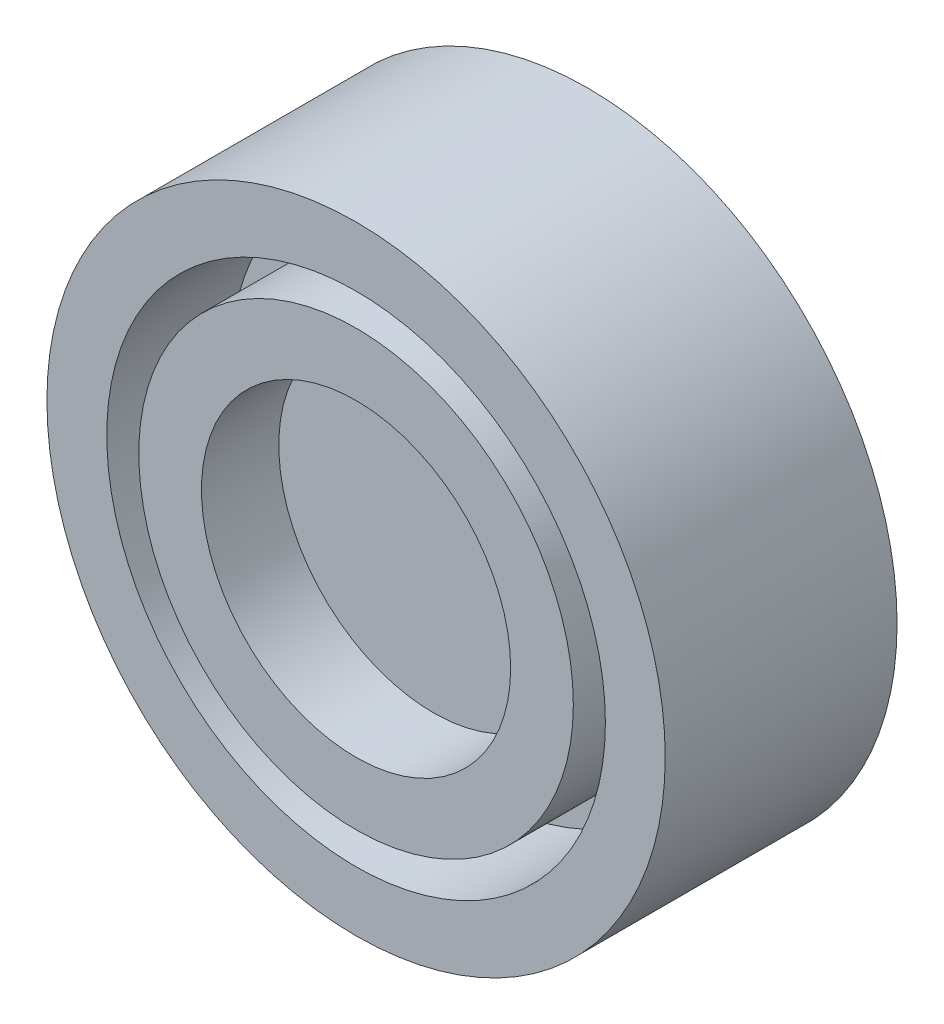
SolidWorks part; units mm, degrees
material "PE High Density"
ref_plane "Front" through (0, 0, 0) normal (0, 0, 1) x (1, 0, 0)
ref_plane "Top" through (0, 0, 0) normal (0, 1, 0) x (1, 0, 0)
ref_plane "Right" through (0, 0, 0) normal (1, 0, 0) x (0, 0, -1)
sketch "Sketch1" plane through (0, 0, 0) normal (0, 0, 1) x (1, 0, 0)
  circle A0 centre (0, 0) radius 20
extrude "Boss-Extrude1" add sketch "Sketch1" along normal blind 15
sketch "Sketch2" plane through (0, 0, 15) normal (0, 0, 1) x (1, 0, 0)
  circle A0 centre (0, 0) radius 10
extrude "Cut-Extrude1" cut sketch "Sketch2" against normal blind 5
sketch "Sketch3" plane through (0, 0, 15) normal (0, 0, 1) x (1, 0, 0)
  circle A0 centre (0, 0) radius 14.0559
  circle A1 centre (0, 0) radius 16.1295
extrude "Cut-Extrude2" cut sketch "Sketch3" against normal blind 8
